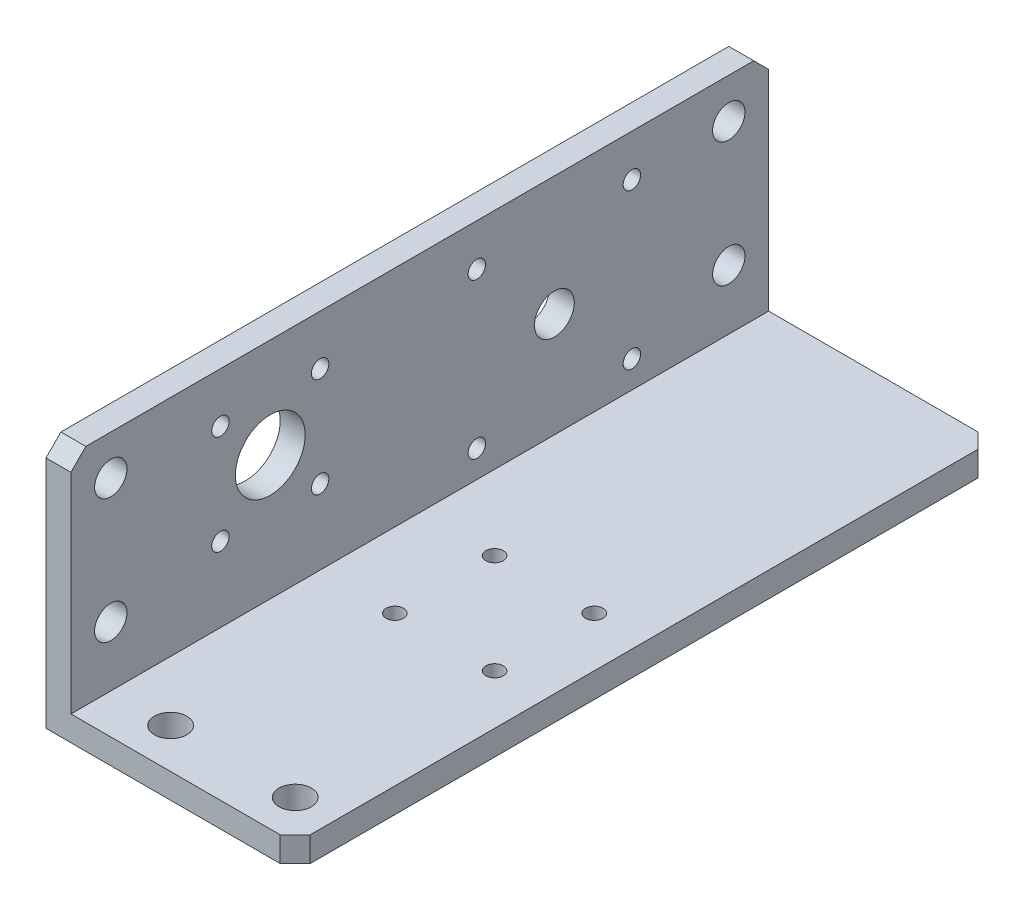
SolidWorks part; units mm, degrees
material "Lega 1060"
ref_plane "Piano frontale" through (0, 0, 0) normal (0, 0, 1) x (1, 0, 0)
ref_plane "Piano superiore" through (0, 0, 0) normal (0, 1, 0) x (1, 0, 0)
ref_plane "Piano destro" through (0, 0, 0) normal (1, 0, 0) x (0, 0, -1)
sketch "Schizzo1" plane through (0, 0, 0) normal (0, 0, 1) x (1, 0, 0)
  line L0 (0, 0) -> (0, 50)
  line L1 (0, 50) -> (5, 50)
  line L2 (5, 50) -> (5, 5)
  line L3 (5, 5) -> (50, 5)
  line L4 (50, 5) -> (50, 0)
  line L5 (50, 0) -> (0, 0)
  dimension "D1" = 5
  dimension "D2" = 5
  dimension "D3" = 50
  dimension "D4" = 50
extrude "Estrusione-Estrusione1" add sketch "Schizzo1" along normal blind 140
sketch "Schizzo2" plane through (0, 0, 0) normal (0, -1, 0) x (1, 0, 0)
  line L0 (5.4524, 132) -> (42.7933, 132) construction
  line L1 (0, 140) -> (50, 140) construction
  line L5 (50, 140) -> (50, 0) construction
  point P4 (17, 132)
  point P5 (42, 132)
  dimension "D1" = 8
  dimension "D2" = 25
  dimension "D3" = 8
sketch "Schizzo3" plane through (0, 0, 0) normal (-1, 0, 0) x (0, 0, 1)
  line L0 (132, 44.621) -> (132, 5.772) construction
  line L1 (140, 50) -> (140, 0) construction
  line L2 (140, 50) -> (0, 50) construction
  point P4 (132, 42)
  point P5 (132, 17)
  dimension "D1" = 8
  dimension "D2" = 8
  dimension "D3" = 25
hole_wizard "Foro Ø6.5 (6.5)-1" positions "Schizzo5" profile "Schizzo4" hole size "Ø6.5" standard "ISO" end condition through all
sketch "Schizzo5" plane through (0, 0, 0) normal (0, -1, 0) x (-1, 0, 0)
  point P0 (-17, -132)
  point P3 (-42, -132)
sketch "Schizzo4" plane through (17, 0, 132) normal (1, 0, 0) x (0, 0, -1)
  line L0 (0, 0) -> (0, 50)
  line L1 (0, 50) -> (3.25, 50)
  line L2 (3.25, 50) -> (3.25, 0)
  line L5 (3.25, 0) -> (0, 0)
  line L11 (0, -6.35) -> (0, 107.95) construction
  dimension "Thru Hole Dia." = 6.5
  dimension "Thru Hole Depth" = 50
hole_wizard "Foro Ø6.5 (6.5)-2" positions "Schizzo7" profile "Schizzo6" hole size "Ø6.5" standard "ISO"
sketch "Schizzo7" plane through (0, 0, 0) normal (-1, 0, 0) x (0, 0, 1)
  point P1 (132, 42)
  point P4 (132, 17)
sketch "Schizzo6" plane through (0, 42, 132) normal (0, 1, 0) x (0, 0, 1)
  line L0 (0, 0) -> (0, 6.9528)
  line L1 (0, 6.9528) -> (3.25, 5)
  line L2 (3.25, 5) -> (3.25, 0)
  line L5 (3.25, 0) -> (0, 0)
  line L10 (0, 6.9528) -> (-3.25, 5) construction
  line L11 (0, -6.35) -> (0, 107.95) construction
  dimension "Hole Dia." = 6.5
  dimension "Hole Depth" = 5
  dimension "Drill Angle" = 118
ref_plane "Piano1" through (0, 0, 70) normal (0, 0, 1) x (1, 0, 0)
mirror "Specchia1" about plane through (0, 0, 70) normal (0, 0, 1) of "Foro Ø6.5 (6.5)-2"
sketch "Schizzo8" plane through (0, 0, 0) normal (0, -1, 0) x (1, 0, 0)
  line L0 (30, 80) -> (7.0316, 80) construction
  line L1 (30, 80) -> (-7.1051, 42.8949) construction
  line L2 (0, 140) -> (50, 140) construction
  line L3 (50, 140) -> (50, 0) construction
  circle A0 centre (20, 70) radius 1.75
  circle A1 centre (20, 90) radius 1.75
  circle A2 centre (40, 90) radius 1.75
  circle A3 centre (40, 70) radius 1.75
  point P18 (30, 80)
  dimension "D3" = 3.5
  dimension "D1" = 60
  dimension "D2" = 20
  dimension "D4" = 45
  dimension "D5" = 20
  dimension "D6" = 4
extrude "Taglio-Estrusione1" cut sketch "Schizzo8" against normal up to next
sketch "Schizzo9" plane through (0, 0, 0) normal (-1, 0, 0) x (0, 0, 1)
  line L0 (100, 44.574) -> (100, 30) construction
  line L1 (100, 30) -> (63.014, 66.986) construction
  line L2 (140, 50) -> (0, 50) construction
  line L3 (140, 50) -> (140, 0) construction
  circle A0 centre (90, 40) radius 1.75
  circle A1 centre (110, 40) radius 1.75
  circle A2 centre (110, 20) radius 1.75
  circle A3 centre (90, 20) radius 1.75
  circle A4 centre (100, 30) radius 7
  point P18 (100, 30)
  dimension "D4" = 3.5
  dimension "D7" = 14
  dimension "D1" = 20
  dimension "D2" = 40
  dimension "D3" = 45
  dimension "D5" = 20
  dimension "D6" = 4
extrude "Taglio-Estrusione2" cut sketch "Schizzo9" against normal up to next
sketch "Schizzo11" plane through (0, 0, 0) normal (-1, 0, 0) x (0, 0, 1)
  line L0 (32.6037, 26) -> (56.4009, 26) construction
  line L1 (43, 26) -> (60.7893, 43.7893) construction
  line L2 (140, 0) -> (0, 0) construction
  circle A0 centre (43, 26) radius 4
  circle A2 centre (58.5563, 41.5563) radius 1.75
  circle A3 centre (58.5563, 10.4437) radius 1.75
  circle A4 centre (27.4437, 10.4437) radius 1.75
  circle A5 centre (27.4437, 41.5563) radius 1.75
  circle A6 centre (100, 30) radius 7 construction
  point P20 (43, 26)
  dimension "D2" = 57
  dimension "D3" = 8
  dimension "D5" = 3.5
  dimension "D1" = 45
  dimension "D4" = 26
  dimension "D6" = 22
  dimension "D7" = 4
extrude "Taglio-Estrusione4" cut sketch "Schizzo11" against normal up to next
chamfer "Smusso1" distance 3 angle 45 4 edges at (50, 2.5, 0) (2.5, 50, 0) (2.5, 50, 140) (50, 2.5, 140)
